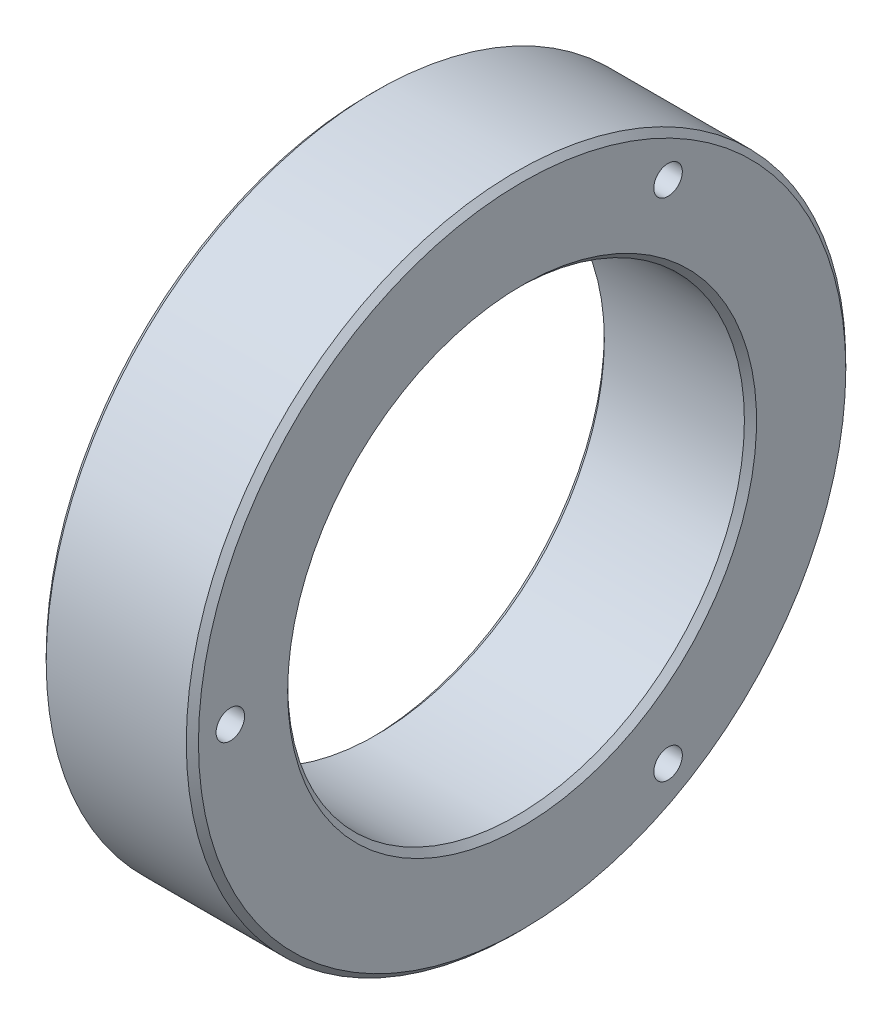
SolidWorks part; units mm, degrees
ref_plane "Front Plane" through (0, 0, 0) normal (1, 0, 0) x (0, 1, 0)
ref_plane "Top Plane" through (0, 0, 0) normal (0, 0, 1) x (0, 1, 0)
ref_plane "Right Plane" through (0, 0, 0) normal (0, 1, 0) x (-1, 0, 0)
sketch "Sketch1" plane through (0, 0, 0) normal (0, 0, 1) x (0, 1, 0)
  line L0 (82.5246, 0) -> (82.5246, -38.1)
  line L1 (82.5246, -38.1) -> (57.15, -38.1)
  line L2 (57.15, -38.1) -> (57.15, 0)
  line L3 (57.15, 0) -> (82.5246, 0)
  line L4 (0, 25.4) -> (0, -63.5) construction
revolve "Revolve1" add sketch "Sketch1" angle 360 about L4
chamfer "Chamfer1" distance 1.524 angle 45 4 edges at (38.1, 0, 57.15) (0, 0, 57.15) (38.1, 0, 82.5246) (0, 0, 82.5246)
sketch "Sketch2" plane through (0, 0, 0) normal (1, 0, 0) x (0, 1, 0)
  circle A0 centre (0, 73.025) radius 3.5687
extrude "Cut-Extrude2" cut sketch "Sketch2" along normal blind 76.2
sketch "Sketch3" plane through (0, 0, 0) normal (1, 0, 0) x (0, 1, 0)
  circle A0 centre (0, 73.025) radius 5.5626
extrude "Cut-Extrude4" cut sketch "Sketch3" along normal blind 9.652
sketch "Sketch4" plane through (0, 0, 0) normal (1, 0, 0) x (0, 1, 0)
  circle A0 centre (-63.246, -36.5252) radius 3.5687
extrude "Cut-Extrude6" cut sketch "Sketch4" along normal blind 76.2
sketch "Sketch5" plane through (0, 0, 0) normal (1, 0, 0) x (0, 1, 0)
  circle A0 centre (-63.246, -36.5252) radius 5.5626
extrude "Cut-Extrude8" cut sketch "Sketch5" along normal blind 9.652
sketch "Sketch6" plane through (0, 0, 0) normal (1, 0, 0) x (0, 1, 0)
  circle A0 centre (63.246, -36.5252) radius 3.5687
extrude "Cut-Extrude10" cut sketch "Sketch6" along normal blind 76.2
sketch "Sketch7" plane through (0, 0, 0) normal (1, 0, 0) x (0, 1, 0)
  circle A0 centre (63.246, -36.5252) radius 5.5626
extrude "Cut-Extrude12" cut sketch "Sketch7" along normal blind 9.652
sketch "Sketch8" plane through (0, 0, 0) normal (1, 0, 0) x (0, 1, 0)
  circle A0 centre (-69.85, 0) radius 3.9687
extrude "Cut-Extrude14" cut sketch "Sketch8" along normal blind 25.4
sketch "Sketch9" plane through (0, 0, 0) normal (1, 0, 0) x (0, 1, 0)
  circle A0 centre (69.85, 0) radius 3.9687
extrude "Cut-Extrude16" cut sketch "Sketch9" along normal blind 25.4
